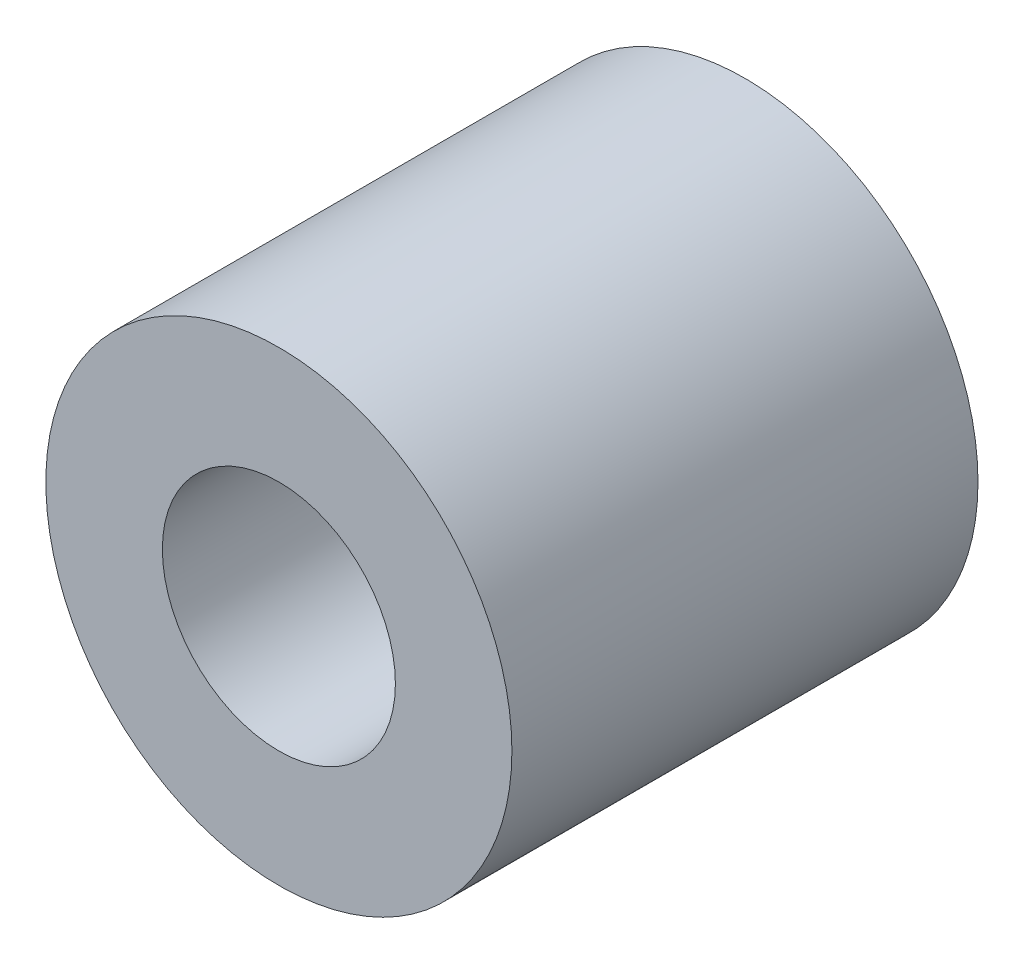
SolidWorks part; units mm, degrees
ref_plane "Piano frontale" through (0, 0, 0) normal (0, 0, 1) x (1, 0, 0)
ref_plane "Piano superiore" through (0, 0, 0) normal (0, 1, 0) x (1, 0, 0)
ref_plane "Piano destro" through (0, 0, 0) normal (1, 0, 0) x (0, 0, -1)
sketch "Schizzo1" plane through (0, 0, 0) normal (0, 0, 1) x (1, 0, 0)
  circle A0 centre (0, 0) radius 5
  circle A1 centre (0, 0) radius 2.5
  dimension "D1" = 10
extrude "Estrusione-Estrusione1" add sketch "Schizzo1" against normal blind 10
